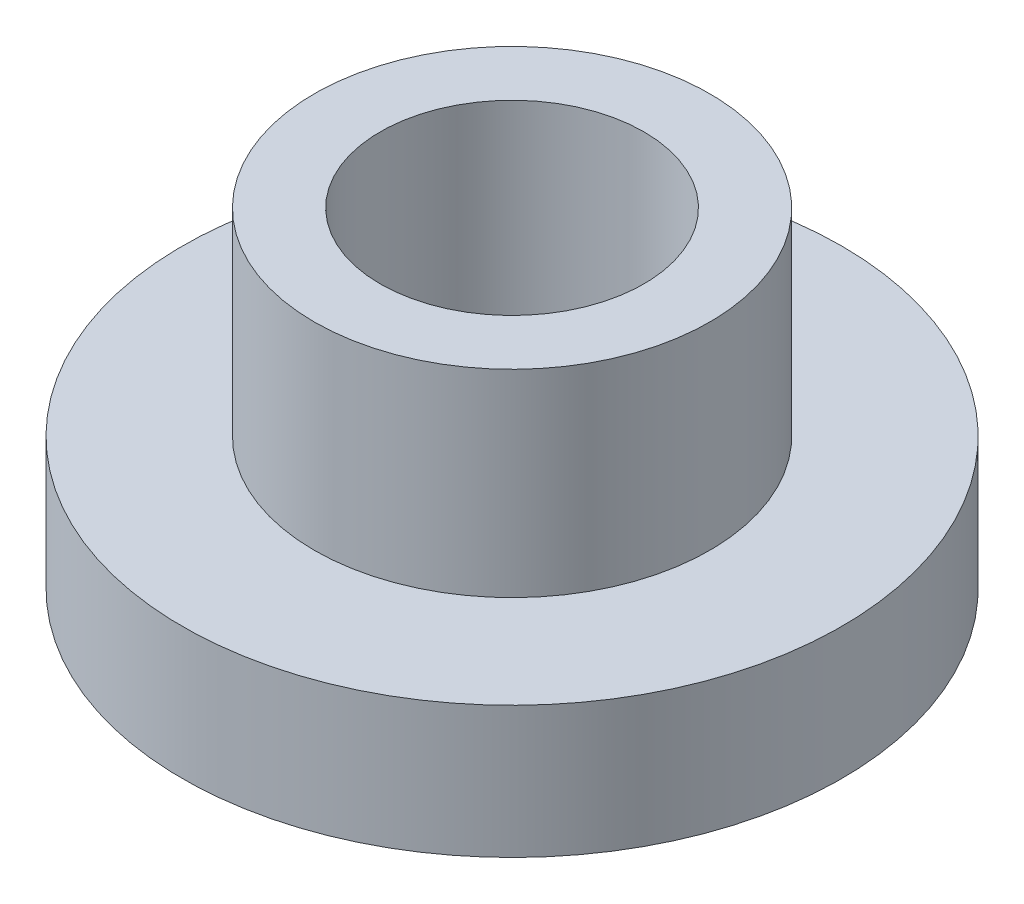
SolidWorks part; units mm, degrees
material "ABS"
ref_plane "前视基准面" through (0, 0, 0) normal (0, 0, 1) x (1, 0, 0)
ref_plane "上视基准面" through (0, 0, 0) normal (0, 1, 0) x (1, 0, 0)
ref_plane "右视基准面" through (0, 0, 0) normal (1, 0, 0) x (0, 0, -1)
sketch "草图1" plane through (0, 0, 0) normal (0, 1, 0) x (1, 0, 0)
  circle A0 centre (0, 0) radius 1.5
  circle A1 centre (0, 0) radius 1
  dimension "D1" = 3
  dimension "D2" = 2
extrude "凸台-拉伸1" add sketch "草图1" along normal blind 1.5
sketch "草图2" plane through (0, 0, 0) normal (0, -1, 0) x (1, 0, 0)
  circle A0 centre (0, 0) radius 2.5
  dimension "D1" = 5
extrude "凸台-拉伸2" add sketch "草图2" along normal blind 1
